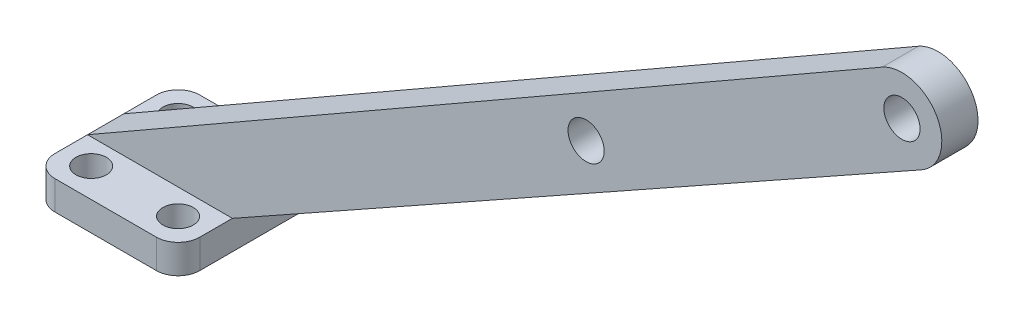
SolidWorks part; units mm, degrees
ref_plane "Front Plane" through (0, 0, 0) normal (0, 0, 1) x (1, 0, 0)
ref_plane "Top Plane" through (0, 0, 0) normal (0, 1, 0) x (1, 0, 0)
ref_plane "Right Plane" through (0, 0, 0) normal (1, 0, 0) x (0, 0, -1)
sketch "Sketch1" plane through (0, 0, 0) normal (0, 0, 1) x (1, 0, 0)
  line L3 (10, 0) -> (-10, 0)
  line L5 (105.1308, 53.3632) -> (10, 0)
  line L6 (-10, 0) -> (99.7033, 62.9308)
  line L7 (10, 0) -> (102.44, 0) construction
  line L8 (102.44, 0) -> (102.44, 58.16) construction
  circle A1 centre (102.44, 58.16) radius 2.5
  arc A2 (105.1308, 53.3632) -> (99.7033, 62.9308) centre (102.44, 58.16) ccw
  point P7 (0, 0)
  dimension "D1" = 5.5
  dimension "D2" = 5
  dimension "D3" = 20
  dimension "D4" = 92.44
  dimension "D5" = 58.16
extrude "Boss-Extrude1" add sketch "Sketch1" along normal blind 5
sketch "Sketch4" plane through (0, 0, 0) normal (0, -1, 0) x (1, 0, 0)
  line L0 (0, 5) -> (0, 0) construction
  line L1 (-10, 5) -> (10, 5) construction
  line L2 (-10, 0) -> (10, 0) construction
  line L3 (-10, 8.5) -> (10, 8.5) construction
  line L4 (7, -7.5) -> (-7, -7.5)
  line L5 (10, -4.5) -> (10, 9.5)
  line L6 (7, 12.5) -> (-7, 12.5)
  line L7 (-10, -4.5) -> (-10, 9.5)
  line L8 (10, -7.5) -> (-10, 12.5) construction
  line L9 (10, 12.5) -> (-10, -7.5) construction
  line L10 (0, 2.5) -> (10, 2.5) construction
  circle A0 centre (-6, 8.5) radius 2.1
  circle A1 centre (5.9999, 8.5) radius 2.1
  circle A2 centre (5.9999, -3.5) radius 2.1
  circle A3 centre (-6, -3.5) radius 2.1
  arc A4 (-7, -7.5) -> (-10, -4.5) centre (-7, -4.5) cw
  arc A5 (7, -7.5) -> (10, -4.5) centre (7, -4.5) ccw
  arc A6 (10, 9.5) -> (7, 12.5) centre (7, 9.5) ccw
  arc A7 (-10, 9.5) -> (-7, 12.5) centre (-7, 9.5) cw
  point P6 (0, 2.5)
  dimension "D3" = 4.2
  dimension "D7" = 3
  dimension "D1" = 20
  dimension "D2" = 20
  dimension "D4" = 4
  dimension "D5" = 4
  dimension "D6" = 11.9999
extrude "Boss-Extrude3" add sketch "Sketch4" along normal blind 4
sketch "Sketch5" plane through (0, 0, 5) normal (0, 0, 1) x (1, 0, 0)
  line L0 (58.8323, 33.6985) -> (102.44, 58.16) construction
  line L1 (10, 0) -> (105.1308, 53.3632) construction
  circle A0 centre (58.8323, 33.6985) radius 2.5
  dimension "D1" = 5
  dimension "D2" = 50
extrude "Cut-Extrude1" cut sketch "Sketch5" against normal blind 10
